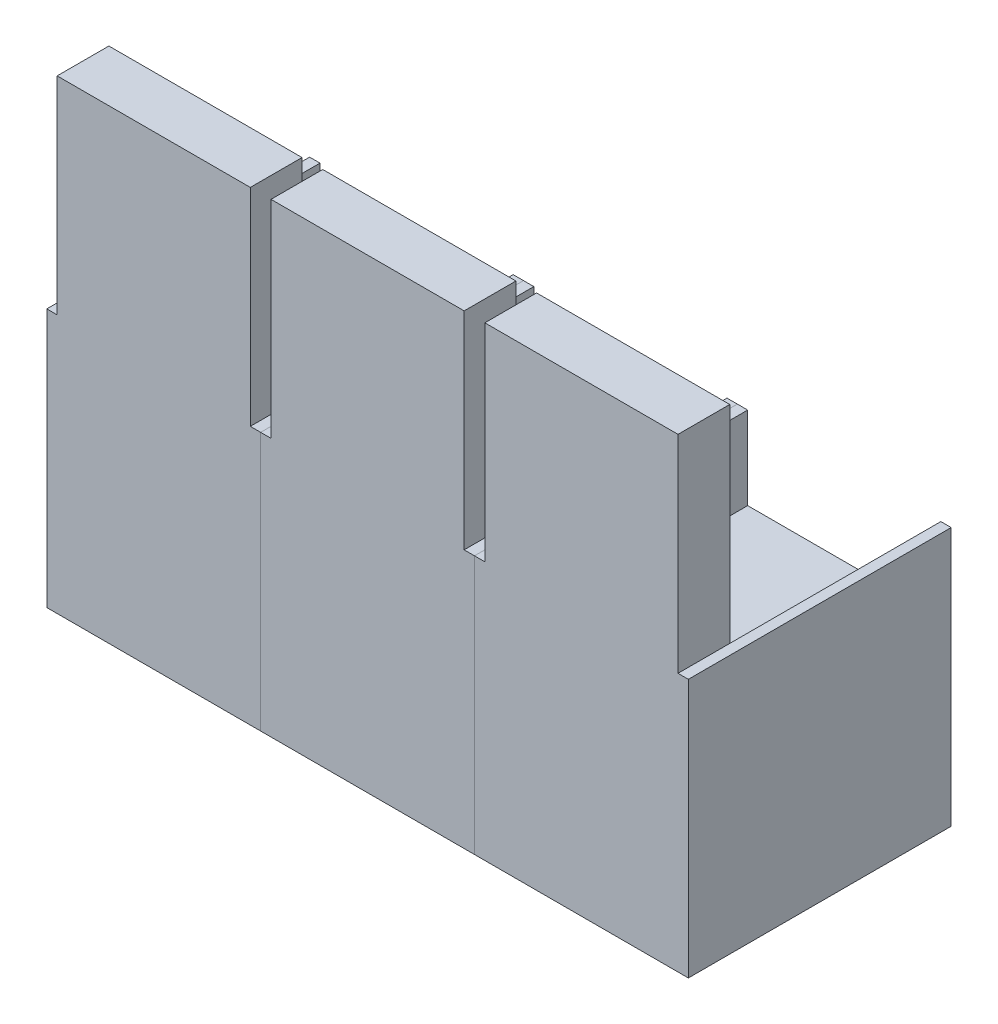
SolidWorks part; units mm, degrees
ref_plane "Front Plane" through (0, 0, 0) normal (0, 0, 1) x (1, 0, 0)
ref_plane "Top Plane" through (0, 0, 0) normal (0, 1, 0) x (1, 0, 0)
ref_plane "Right Plane" through (0, 0, 0) normal (1, 0, 0) x (0, 0, -1)
sketch "Sketch1" plane through (0, 0, 0) normal (0, 1, 0) x (1, 0, 0)
  line L1 (-395.8039, 0) -> (129.1294, 0)
  line L2 (-395.8039, 0) -> (-395.8039, -645.16)
  line L3 (-395.8039, -645.16) -> (129.1294, -645.16)
  line L4 (129.1294, 0) -> (129.1294, -645.16)
  dimension "D1" = 645.16
  dimension "D2" = 524.9333
extrude "Boss-Extrude1" add sketch "Sketch1" along normal blind 431.8
sketch "Sketch2" plane through (0, 431.8, 0) normal (0, 1, 0) x (1, 0, 0)
  line L0 (-395.8039, -645.16) -> (129.1294, -645.16) construction
  line L1 (-395.8039, 0) -> (-370.4039, 0)
  line L2 (-395.8039, 0) -> (-395.8039, -645.16)
  line L3 (-395.8039, -645.16) -> (-370.4039, -645.16)
  line L4 (-370.4039, 0) -> (-370.4039, -645.16)
  line L6 (129.1294, 0) -> (103.7294, 0)
  line L7 (129.1294, 0) -> (129.1294, -645.16)
  line L8 (129.1294, -645.16) -> (103.7294, -645.16)
  line L9 (103.7294, 0) -> (103.7294, -645.16)
  dimension "D1" = 25.4
extrude "Boss-Extrude2" add sketch "Sketch2" along normal blind 203.2
sketch "Sketch3" plane through (0, 431.8, 0) normal (0, 1, 0) x (1, 0, 0)
  line L0 (-370.4039, -645.16) -> (-370.4039, 0) construction
  line L1 (-370.4039, -518.16) -> (103.7294, -518.16)
  line L2 (-370.4039, -518.16) -> (-370.4039, -645.16)
  line L3 (-370.4039, -645.16) -> (103.7294, -645.16)
  line L4 (103.7294, -518.16) -> (103.7294, -645.16)
  dimension "D1" = 127
extrude "Boss-Extrude3" add sketch "Sketch3" along normal blind 711.2
pattern_linear "LPattern1" count 3 spacing 524.9333 along (1, 0, 0) of bodies 103
